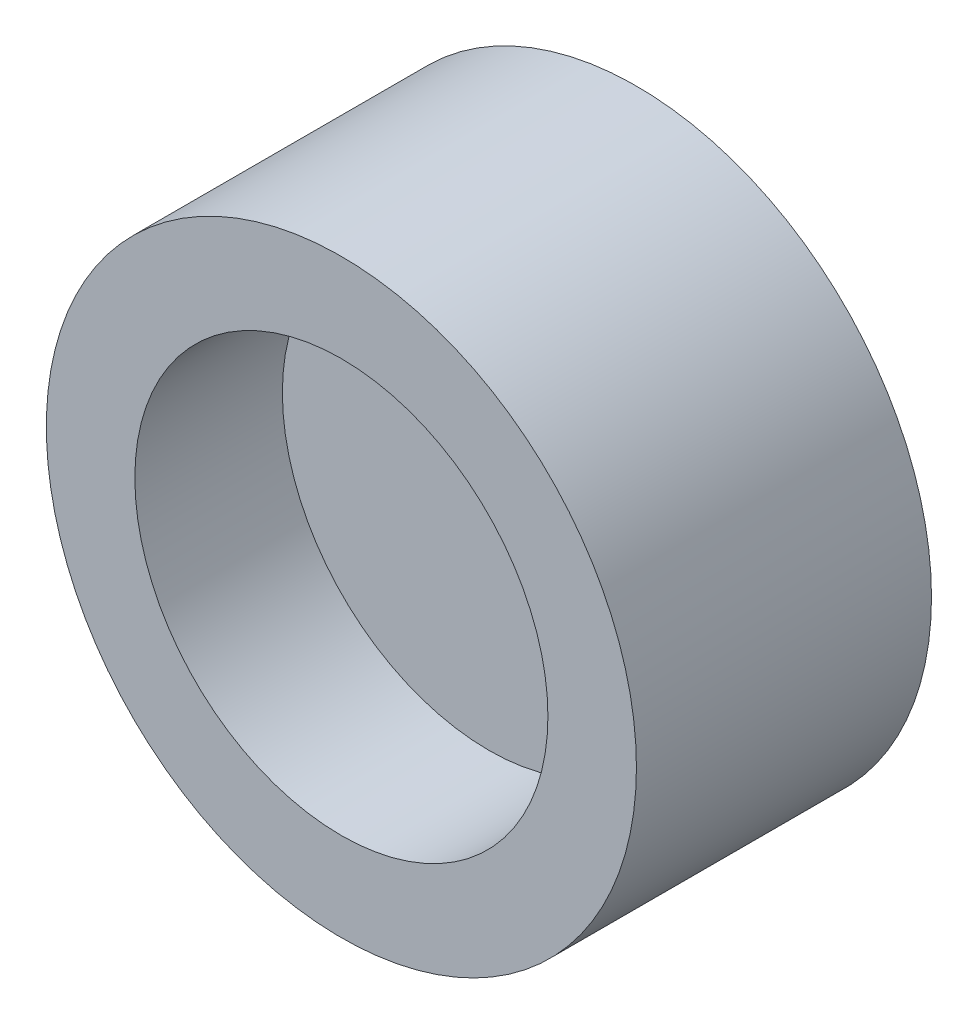
SolidWorks part; units mm, degrees
ref_plane "Front" through (0, 0, 0) normal (0, 0, 1) x (1, 0, 0)
ref_plane "Top" through (0, 0, 0) normal (0, 1, 0) x (1, 0, 0)
ref_plane "Right" through (0, 0, 0) normal (1, 0, 0) x (0, 0, -1)
sketch "Эскиз1" plane through (0, 0, 0) normal (0, 0, 1) x (1, 0, 0)
  circle A0 centre (0, 0) radius 3
extrude "Бобышка-Вытянуть1" add sketch "Эскиз1" along normal blind 3
sketch "Эскиз2" plane through (0, 0, 3) normal (0, 0, 1) x (1, 0, 0)
  circle A0 centre (0, 0) radius 2.1
extrude "Вырез-Вытянуть1" cut sketch "Эскиз2" against normal blind 1.5
